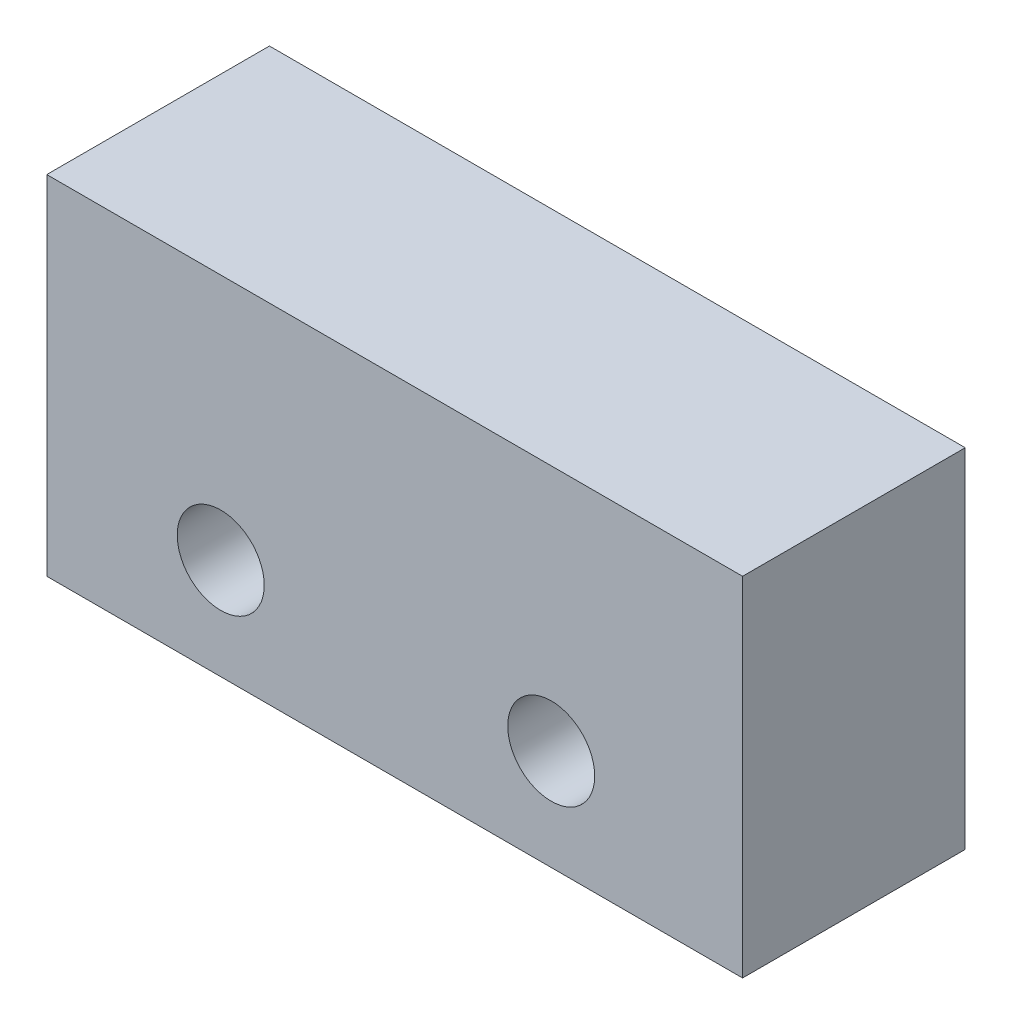
SolidWorks part; units mm, degrees
ref_plane "Front Plane" through (0, 0, 0) normal (0, 0, 1) x (1, 0, 0)
ref_plane "Top Plane" through (0, 0, 0) normal (0, 1, 0) x (1, 0, 0)
ref_plane "Right Plane" through (0, 0, 0) normal (1, 0, 0) x (0, 0, -1)
sketch "Sketch1" plane through (0, 0, 0) normal (0, 0, 1) x (1, 0, 0)
  line L1 (-10, -5) -> (10, -5)
  line L2 (-10, -5) -> (-10, 5)
  line L3 (-10, 5) -> (10, 5)
  line L4 (10, -5) -> (10, 5)
  line L5 (-10, -5) -> (10, 5) construction
  line L6 (-10, 5) -> (10, -5) construction
  circle A0 centre (-5, -2.1) radius 1.25
  circle A1 centre (4.5, -2.1) radius 1.25
  point P0 (0, 0)
  point P10 (0, 0)
  point P11 (-3.079, -7.139)
  point P12 (-7.0724, -2.0808)
  point P13 (7.5366, -2.1)
  point P14 (5.5732, -2.1)
  dimension "D3" = 2.5
  dimension "D1" = 20
  dimension "D2" = 10
  dimension "D4" = 2.9
  dimension "D5" = 9.5
  dimension "D6" = 14.5
extrude "Boss-Extrude1" add sketch "Sketch1" along normal blind 6.4
